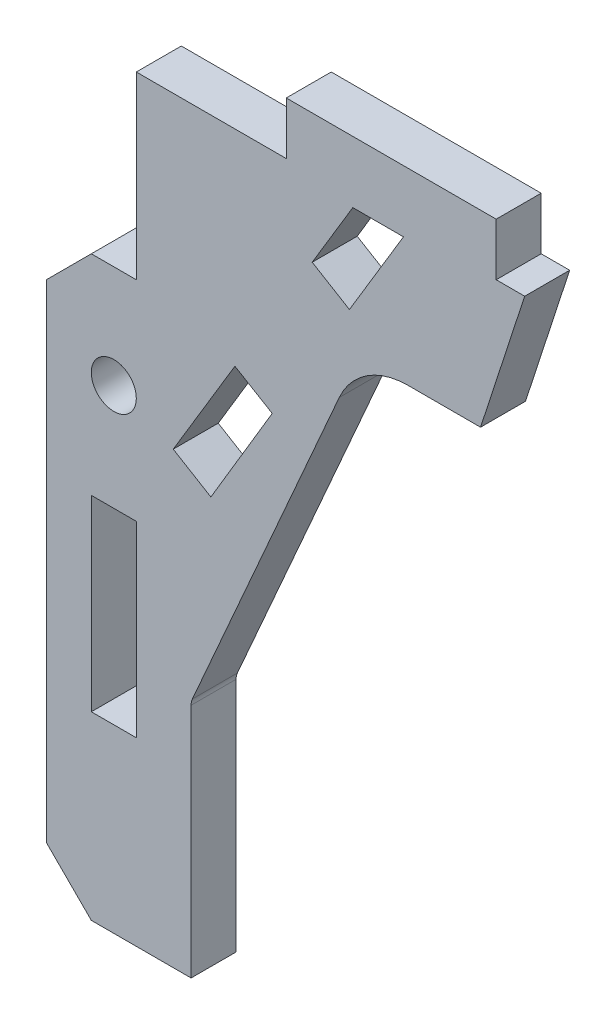
SolidWorks part; units mm, degrees
ref_plane "前视基准面" through (0, 0, 0) normal (0, 0, 1) x (1, 0, 0)
ref_plane "上视基准面" through (0, 0, 0) normal (0, 1, 0) x (1, 0, 0)
ref_plane "右视基准面" through (0, 0, 0) normal (1, 0, 0) x (0, 0, -1)
sketch "草图1" plane through (0, 0, 0) normal (0, 0, 1) x (1, 0, 0)
  line L1 (-25.4, 4.5488) -> (-22.4, 4.5488)
  line L3 (-25.4, -7.9512) -> (-25.4, 4.5488)
  line L5 (-22.4, 4.5488) -> (-22.4, -7.9512)
  line L7 (-22.4, -7.9512) -> (-25.4, -7.9512)
  line L9 (-0.9434, 20.7231) -> (-16.494, -16.074)
  line L11 (7.4, 21.9445) -> (0.8988, 21.9445)
  line L13 (9.4, 19.9445) -> (9.4, -20.3777)
  line L15 (-16.6475, -16.7224) -> (-16.8775, -20.2475)
  line L17 (-14.8817, -22.3777) -> (7.4, -22.3777)
  line L44 (-28.4, -17) -> (-25.4, -20)
  line L45 (-25.4, -20) -> (-22.4, -20)
  line L46 (-22.4, -20) -> (-22.4, -27.5)
  line L47 (-22.4, -27.5) -> (17.4, -27.5)
  line L48 (17.4, -27.5) -> (17.4, -20)
  line L49 (17.4, -20) -> (22.4, -20)
  line L50 (22.4, -20) -> (22.4, -5)
  line L51 (22.4, -5) -> (17.4, -5)
  line L52 (17.4, -5) -> (17.4, 10)
  line L53 (17.4, 10) -> (22.4, 10)
  line L54 (22.4, 10) -> (22.4, 20)
  line L55 (22.4, 20) -> (17.4, 20)
  line L56 (17.4, 20) -> (17.4, 30.5)
  line L57 (17.4, 30.5) -> (1.6, 30.5)
  line L58 (1.6, 30.5) -> (1.6, 34)
  line L59 (1.6, 34) -> (-12.4, 34)
  line L60 (-12.4, 34) -> (-12.4, 30.5)
  line L61 (-12.4, 30.5) -> (-22.4, 30.5)
  line L62 (-22.4, 30.5) -> (-22.4, 18.5)
  line L63 (-22.4, 18.5) -> (-25.4, 18.5)
  line L64 (-25.4, 18.5) -> (-28.4, 15.5)
  line L65 (-28.4, 15.5) -> (-28.4, -17)
  circle A1 centre (-23.9, 11.6451) radius 1.5
  arc A3 (0.8988, 21.9445) -> (-0.9434, 20.7231) centre (0.8988, 19.9445) ccw
  arc A5 (9.4, 19.9445) -> (7.4, 21.9445) centre (7.4, 19.9445) ccw
  arc A7 (-16.494, -16.074) -> (-16.6475, -16.7224) centre (-14.6518, -16.8525) ccw
  arc A9 (-16.8775, -20.2475) -> (-14.8817, -22.3777) centre (-14.8817, -20.3777) ccw
  arc A11 (7.4, -22.3777) -> (9.4, -20.3777) centre (7.4, -20.3777) ccw
extrude "凸台-拉伸1" add sketch "草图1" along normal blind 3
sketch "草图2" plane through (22.4, 0, 0) normal (1, 0, 0) x (0, 0, -1)
  line L4 (0, -20) -> (0, -5)
  line L5 (0, -5) -> (-3, -5)
  line L6 (-3, -5) -> (-3, -20)
  line L7 (-3, -20) -> (0, -20)
  line L8 (0, -20) -> (0, -5)
  line L9 (0, -5) -> (-3, -5)
  line L10 (-3, -5) -> (-3, -20)
  line L11 (-3, -20) -> (0, -20)
  line L12 (0, 10) -> (0, 20)
  line L13 (0, 20) -> (-3, 20)
  line L14 (-3, 20) -> (-3, 10)
  line L15 (-3, 10) -> (0, 10)
  line L16 (0, 10) -> (0, 20)
  line L17 (0, 20) -> (-3, 20)
  line L18 (-3, 20) -> (-3, 10)
  line L19 (-3, 10) -> (0, 10)
  dimension "D1" = 0
  dimension "D2" = 0
extrude "切除-拉伸1" cut sketch "草图2" against normal up to surface (5 mm away) up to face at (17.4, 2.5, 1.5)
sketch "草图4" plane through (0, 0, 0) normal (0, 0, -1) x (-1, 0, 0)
  line L0 (-7.4, 21.9445) -> (-17.4, 21.9445)
  line L1 (-17.4, -27.5) -> (-17.4, 30.5) construction
  line L2 (-17.4, 21.9445) -> (-17.4, 1.5)
  line L3 (-17.4, 1.5) -> (-9.4, 1.5)
  line L4 (-9.4, -20.3777) -> (-9.4, 19.9445) construction
  line L5 (-9.4, 1.5) -> (-7.4, 21.9445)
extrude "切除-拉伸2" cut sketch "草图4" against normal through all
sketch "草图5" plane through (0, 0, 0) normal (0, 0, -1) x (-1, 0, 0)
  line L0 (-7.4, -22.3777) -> (-17.4, -22.3777)
  line L1 (-17.4, -27.5) -> (-17.4, 1.5) construction
  line L2 (-17.4, -22.3777) -> (-17.4, 1.5)
  line L3 (-17.4, 1.5) -> (-9.4, 1.5)
  line L4 (-9.4, 1.5) -> (-7.4, -22.3777)
extrude "切除-拉伸3" cut sketch "草图5" against normal blind 10
sketch "草图6" plane through (0, 0, 0) normal (0, 0, -1) x (-1, 0, 0)
  line L0 (-0.8988, 21.9445) -> (10.5413, 21.9445)
  line L1 (10.5413, 21.9445) -> (16.598, -16.3917)
  line L2 (16.598, -16.3917) -> (-0.8988, 21.9445)
  arc A0 (16.6475, -16.7224) -> (16.494, -16.074) centre (14.6518, -16.8525) ccw construction
extrude "切除-拉伸4" cut sketch "草图6" against normal blind 10
sketch "草图8" plane through (0, 0, 0) normal (0, 0, -1) x (-1, 0, 0)
  line L0 (14.8817, -22.3777) -> (-17.4, -22.3777) construction
  line L1 (14.8817, -22.3777) -> (-17.4, -22.3777)
  line L2 (16.6475, -16.7224) -> (16.8775, -20.2475) construction
  line L3 (16.6475, -16.7224) -> (16.8775, -20.2475)
  line L4 (16.6475, -16.7224) -> (-17.4, -16.7224)
  line L5 (-17.4, -16.7224) -> (-17.4, -22.3777)
  arc A0 (14.8817, -22.3777) -> (16.8775, -20.2475) centre (14.8817, -20.3777) ccw construction
  arc A1 (14.8817, -22.3777) -> (16.8775, -20.2475) centre (14.8817, -20.3777) ccw
extrude "凸台-拉伸2" add sketch "草图8" against normal up to surface (3 mm away) up to face at (-10.7245, 3.6115, 3)
sketch "草图9" plane through (0, 0, 0) normal (0, 0, -1) x (-1, 0, 0)
  line L0 (16.6475, -16.7224) -> (-17.4, -16.7224) construction
  line L1 (16.6475, -16.7224) -> (-17.4, -16.7224)
  line L2 (16.598, -16.3917) -> (-17.4, -16.3917)
  line L3 (-17.4, -16.3917) -> (-17.4, -16.7224)
  arc A0 (16.6475, -16.7224) -> (16.598, -16.3917) centre (14.6518, -16.8525) ccw construction
  arc A1 (16.6475, -16.7224) -> (16.598, -16.3917) centre (14.6518, -16.8525) ccw
extrude "凸台-拉伸3" add sketch "草图9" against normal up to surface (3 mm away) up to face at (-10.1576, 6.5555, 3)
sketch "草图10" plane through (0, 0, 0) normal (0, 0, -1) x (-1, 0, 0)
  line L2 (16.598, -16.3917) -> (-17.4, -16.3917) construction
  line L3 (16.598, -16.3917) -> (-17.4, -16.3917)
  line L4 (-17.4, -16.3917) -> (-17.4, -18.3917)
  line L5 (16.598, -16.3917) -> (16.9139, -18.3917)
  line L6 (-17.4, -18.3917) -> (16.9139, -18.3917)
extrude "切除-拉伸5" cut sketch "草图10" against normal blind 8
fillet "圆角2" radius 5 1 edges at (-10.5413, 21.9445, 1.5)
sketch "草图11" plane through (0, 0, 0) normal (0, 0, -1) x (-1, 0, 0)
  line L0 (6.2692, 21.9445) -> (11.208, 17.7248)
  arc A0 (11.208, 17.7248) -> (6.2692, 21.9445) centre (6.2692, 16.9445) ccw construction
  arc A1 (11.208, 17.7248) -> (6.2692, 21.9445) centre (6.2692, 16.9445) ccw
extrude "凸台-拉伸4" add sketch "草图11" against normal up to surface (3 mm away) up to face at (-9.7037, 8.2232, 3)
fillet "圆角3" radius 2 2 edges at (-11.208, 17.7248, 1.5) (-6.2692, 21.9445, 1.5)
sketch "草图12" plane through (0, 0, 3) normal (0, 0, 1) x (1, 0, 0)
  line L0 (-6.8304, 21.4651) -> (-10.6468, 18.2042) construction
  line L1 (-7.9817, 20.4813) -> (-10.6468, 18.2042)
  line L2 (-11.3232, 16.9958) -> (-16.9139, -18.3917) construction
  line L3 (-11.3232, 16.9958) -> (-12.3413, 10.5513)
  line L4 (-7.9817, 20.4813) -> (-12.3413, 10.5513)
  arc A0 (-10.6468, 18.2042) -> (-11.3232, 16.9958) centre (-9.3477, 16.6837) ccw construction
  arc A1 (-10.6468, 18.2042) -> (-11.3232, 16.9958) centre (-9.3477, 16.6837) ccw
extrude "凸台-拉伸5" add sketch "草图12" against normal up to surface (3 mm away) up to face at (-23.9, -1.7012, 0)
fillet "圆角4" radius 2 2 edges at (-12.3413, 10.5513, 1.5) (-7.9817, 20.4813, 1.5)
sketch "草图14" plane through (0, 0, 3) normal (0, 0, 1) x (1, 0, 0)
  line L0 (-8.1658, 20.0621) -> (-6.3459, 24.2075)
  line L1 (-6.3459, 24.2075) -> (17.4, 24.2075)
  line L2 (17.4, 21.9445) -> (17.4, 30.5) construction
  line L3 (17.4, 24.2075) -> (17.4, 21.9445)
  line L4 (17.4, 21.9445) -> (-5.5312, 21.9445)
  line L5 (-6.8304, 21.4651) -> (-7.6337, 20.7787) construction
  line L6 (-6.8304, 21.4651) -> (-7.6337, 20.7787)
  arc A0 (-5.5312, 21.9445) -> (-6.8304, 21.4651) centre (-5.5312, 19.9445) ccw construction
  arc A1 (-5.5312, 21.9445) -> (-6.8304, 21.4651) centre (-5.5312, 19.9445) ccw
  arc A2 (-7.6337, 20.7787) -> (-8.1658, 20.0621) centre (-6.3345, 19.2582) ccw construction
  arc A3 (-7.6337, 20.7787) -> (-8.1658, 20.0621) centre (-6.3345, 19.2582) ccw
extrude "切除-拉伸6" cut sketch "草图14" against normal blind 6
sketch "草图15" plane through (0, 0, 3) normal (0, 0, 1) x (1, 0, 0)
  line L0 (17.4, -18.3917) -> (17.4, -22.3917)
  line L1 (17.4, -27.5) -> (17.4, -18.3917) construction
  line L2 (17.4, -22.3917) -> (-17.5459, -22.3917)
  line L3 (-16.9139, -18.3917) -> (17.4, -18.3917) construction
  line L5 (-16.9139, -18.3917) -> (-17.5459, -22.3917)
  line L6 (-16.9139, -18.3917) -> (17.4, -18.3917)
extrude "切除-拉伸7" cut sketch "草图15" against normal blind 10
sketch "草图16" plane through (0, 0, 3) normal (0, 0, 1) x (1, 0, 0)
  line L0 (17.4, -22.3917) -> (17.4, -24.3917)
  line L1 (17.4, -27.5) -> (17.4, -22.3917) construction
  line L2 (17.4, -24.3917) -> (-17.8618, -24.3917)
  line L5 (-17.5459, -22.3917) -> (-17.8618, -24.3917)
  line L6 (-17.5459, -22.3917) -> (17.4, -22.3917) construction
  line L7 (-17.5459, -22.3917) -> (17.4, -22.3917)
extrude "切除-拉伸8" cut sketch "草图16" against normal blind 10
sketch "草图17" plane through (0, 0, 3) normal (0, 0, 1) x (1, 0, 0)
  line L6 (17.4, 24.2075) -> (10.4, 24.2075)
  line L7 (17.4, 24.2075) -> (-6.3459, 24.2075) construction
  line L8 (10.4, 24.2075) -> (10.4, 30.5)
  line L9 (17.4, 30.5) -> (1.6, 30.5) construction
  line L10 (10.4, 30.5) -> (17.4, 30.5)
  line L11 (17.4, 30.5) -> (17.4, 24.2075)
extrude "切除-拉伸9" cut sketch "草图17" against normal blind 5
sketch "草图18" plane through (0, 0, 3) normal (0, 0, 1) x (1, 0, 0)
  line L0 (17.4, -27.5) -> (-2.5, -27.5)
  line L1 (-22.4, -27.5) -> (17.4, -27.5) construction
  line L2 (-2.5, -27.5) -> (-2.5, -24.3917)
  line L3 (-17.8618, -24.3917) -> (17.4, -24.3917) construction
  line L4 (-2.5, -24.3917) -> (17.4, -24.3917)
  line L5 (17.4, -24.3917) -> (17.4, -27.5)
extrude "切除-拉伸10" cut sketch "草图18" against normal through all
sketch "草图19" plane through (0, 0, 3) normal (0, 0, 1) x (1, 0, 0)
  line L0 (10.4, -14.5143) -> (10.4, -27.5)
  line L1 (-2.5, -27.5) -> (10.4, -27.5)
  line L2 (-17.8618, -24.3917) -> (-2.5, -24.3917) construction
  line L3 (-17.8618, -24.3917) -> (-2.5, -24.3917)
  line L4 (-12.3816, 10.296) -> (-17.8618, -24.3917) construction
  line L5 (-16.3013, -14.5143) -> (-17.8618, -24.3917)
  line L6 (-17.8618, -24.3917) -> (-16.3013, -14.5143)
  line L7 (-16.3013, -14.5143) -> (10.4, -14.5143)
  line L8 (-2.5, -27.5) -> (-2.5, -24.3917)
  line M2 (-2.5, -27.5) -> (-2.5, -24.3917)
  line M3 (-2.5, -24.3917) -> (-17.8618, -24.3917)
  line M4 (-17.8618, -24.3917) -> (-12.3816, 10.296)
extrude "凸台-拉伸6" add sketch "草图19" against normal up to surface (3 mm away) contours L7 L1 L0 M4 M3 M2 up to face at (-12.5921, 7.561, 0)
sketch "草图20" plane through (10.4, 0, 0) normal (1, 0, 0) x (0, 0, -1)
  line L4 (-3, -27.5) -> (0, -27.5)
  line L5 (0, -27.5) -> (0, -14.5143)
  line L6 (0, -14.5143) -> (-3, -14.5143)
  line L7 (-3, -14.5143) -> (-3, -27.5)
  line L8 (-3, -27.5) -> (0, -27.5)
  line L9 (0, -27.5) -> (0, -14.5143)
  line L10 (0, -14.5143) -> (-3, -14.5143)
  line L11 (-3, -14.5143) -> (-3, -27.5)
  dimension "D1" = 0
extrude "凸台-拉伸7" add sketch "草图20" along normal blind 7
sketch "草图22" plane through (0, 0, 3) normal (0, 0, 1) x (1, 0, 0)
  line L0 (-22.4, -27.5) -> (17.4, -27.5) construction
  line L1 (-22.4, -27.5) -> (17.4, -27.5)
  line L2 (17.4, -14.5143) -> (17.4, -27.5) construction
  line L3 (17.4, -14.5143) -> (17.4, -27.5)
  line L4 (-16.3013, -14.5143) -> (17.4, -14.5143) construction
  line L5 (-16.3013, -14.5143) -> (17.4, -14.5143)
  line L7 (17.4, -27.5) -> (17.4, -14)
  line L8 (17.4, -14) -> (-16.2201, -14)
  line L9 (-12.3816, 10.296) -> (-16.3013, -14.5143) construction
  line L10 (-16.2201, -14) -> (-16.3013, -14.5143)
  line M1 (17.4, -14.5143) -> (-16.3013, -14.5143)
  line M2 (-16.3013, -14.5143) -> (-12.3816, 10.296)
extrude "凸台-拉伸9" add sketch "草图22" against normal up to surface (3 mm away) contours L7 L8 M2 M1 up to face at (-10.5241, 8.5488, 0)
sketch "草图23" plane through (17.4, 0, 0) normal (1, 0, 0) x (0, 0, -1)
  line L0 (-3, -14) -> (-3, -27.5) construction
  line L1 (-3, -16.75) -> (-3, -24.75)
  line L2 (0, -27.5) -> (0, -14) construction
  line L3 (0, -24.75) -> (0, -16.75)
  line L4 (-3, -20.75) -> (-3, -16.75)
  line L5 (-3, -16.75) -> (0, -16.75)
  line L6 (0, -16.75) -> (0, -24.75)
  line L7 (0, -24.75) -> (-3, -24.75)
  line M1 (-3, -14) -> (-3, -27.5)
  line M3 (0, -27.5) -> (0, -14)
extrude "凸台-拉伸10" add sketch "草图23" along normal blind 5 contours L7 L5 L1 M3 M1
sketch "草图25" plane through (0, 0, 3) normal (0, 0, 1) x (1, 0, 0)
  line L0 (10.4, 24.2075) -> (-6.3459, 24.2075) construction
  line L1 (10.4, 24.2075) -> (-6.3459, 24.2075)
  line L2 (-12.2374, 10.7879) -> (-6.3459, 24.2075) construction
  line L3 (-7.5518, 21.4605) -> (-6.3459, 24.2075)
  line L4 (-6.3459, 24.2075) -> (-7.5518, 21.4605)
  line L5 (-7.5518, 21.4605) -> (10.4, 21.4605)
  line L6 (10.4, 21.4605) -> (10.4, 24.2075)
  line M5 (-12.2374, 10.7879) -> (-6.3459, 24.2075)
  line M6 (-6.3459, 24.2075) -> (10.4, 24.2075)
extrude "凸台-拉伸11" add sketch "草图25" against normal up to surface (3 mm away) contours L5 L6 M6 M5 up to face at (-5.45, 3.7085, 0)
fillet "圆角7" radius 5 1 edges at (-7.5518, 21.4605, 1.5)
sketch "草图26" plane through (0, 0, 3) normal (0, 0, 1) x (1, 0, 0)
  line L2 (-16.2201, -14) -> (-17.4685, -21.902)
  line L3 (-17.4685, -21.902) -> (12.3226, -22.559)
  line L4 (12.3226, -22.559) -> (12.3226, -14)
  line L5 (17.4, -14) -> (-16.2201, -14) construction
  line L6 (12.3226, -14) -> (-16.2201, -14)
extrude "切除-拉伸11" cut sketch "草图26" against normal blind 10
fillet "圆角8" radius 10 1 edges at (-17.4685, -21.902, 1.5)
sketch "草图30" plane through (0, 0, 3) normal (0, 0, 1) x (1, 0, 0)
  line L0 (17.4, -14) -> (12.3226, -14) construction
  line L1 (13.4, -14) -> (12.3226, -14)
  line L3 (13.4, -14) -> (13.4, -22.5658)
  line L4 (13.4, -22.5658) -> (12.3226, -22.559)
  line L5 (12.3226, -22.559) -> (12.3226, -14)
extrude "切除-拉伸13" cut sketch "草图30" against normal blind 10
sketch "草图32" plane through (13.4, 0, 0) normal (-1, 0, 0) x (0, 0, 1)
  line L4 (0, -22.5658) -> (3, -22.5658)
  line L5 (3, -22.5658) -> (3, -14)
  line L6 (3, -14) -> (0, -14)
  line L7 (0, -14) -> (0, -22.5658)
  line L8 (0, -22.5658) -> (3, -22.5658)
  line L9 (3, -22.5658) -> (3, -14)
  line L10 (3, -14) -> (0, -14)
  line L11 (0, -14) -> (0, -22.5658)
  dimension "D1" = 0
extrude "凸台-拉伸12" add sketch "草图32" along normal blind 0.5
fillet "圆角10" radius 3 1 edges at (12.9, -22.5626, 1.5)
sketch "草图33" plane through (10.4, 0, 0) normal (1, 0, 0) x (0, 0, -1)
  line L4 (0, 30.5) -> (-3, 30.5)
  line L5 (-3, 30.5) -> (-3, 21.4605)
  line L6 (-3, 21.4605) -> (0, 21.4605)
  line L7 (0, 21.4605) -> (0, 30.5)
  line L8 (0, 30.5) -> (-3, 30.5)
  line L9 (-3, 30.5) -> (-3, 21.4605)
  line L10 (-3, 21.4605) -> (0, 21.4605)
  line L11 (0, 21.4605) -> (0, 30.5)
  dimension "D1" = 0
extrude "切除-拉伸14" cut sketch "草图33" against normal blind 5
sketch "草图34" plane through (0, 0, 3) normal (0, 0, 1) x (1, 0, 0)
  line L0 (5.4, 30.5) -> (1.6, 30.5) construction
  line L1 (5.4, 30.5) -> (3.5, 30.5)
  line L2 (5.4, 30.5) -> (5.4, 21.4605) construction
  line L3 (5.4, 30.5) -> (5.4, 21.4605)
  line L4 (3.5, 30.5) -> (0.5568, 21.4605)
  line L5 (-4.2863, 21.4605) -> (5.4, 21.4605) construction
  line L6 (0.5568, 21.4605) -> (5.4, 21.4605)
extrude "切除-拉伸15" cut sketch "草图34" against normal blind 10
sketch "草图35" plane through (0, 0, 3) normal (0, 0, 1) x (1, 0, 0)
  line L0 (-15.8049, -12.1577) -> (-15.8035, -27.5)
  line L1 (-22.4, -27.5) -> (17.4, -27.5) construction
  line L2 (-6.0253, -22.1544) -> (9.8339, -22.5041) construction
  line L3 (-6.0253, -22.1544) -> (9.8339, -22.5041)
  line L4 (12.9, -19.5048) -> (12.9, -14) construction
  line L5 (12.9, -19.5048) -> (12.9, -14)
  line L6 (17.4, -14) -> (12.9, -14) construction
  line L7 (17.4, -14) -> (12.9, -14)
  line L8 (17.4, -14) -> (17.4, -16.75) construction
  line L9 (17.4, -14) -> (17.4, -16.75)
  line L10 (22.4, -16.75) -> (17.4, -16.75) construction
  line L11 (22.4, -16.75) -> (17.4, -16.75)
  line L12 (22.4, -16.75) -> (22.4, -24.75) construction
  line L13 (22.4, -16.75) -> (22.4, -24.75)
  line L14 (22.4, -24.75) -> (17.4, -24.75) construction
  line L15 (22.4, -24.75) -> (17.4, -24.75)
  line L16 (17.4, -24.75) -> (17.4, -27.5) construction
  line L17 (17.4, -24.75) -> (17.4, -27.5)
  line L18 (-15.8035, -27.5) -> (17.4, -27.5)
  arc A0 (-15.6823, -10.5963) -> (-6.0253, -22.1544) centre (-5.8049, -12.1568) ccw construction
  arc A1 (-15.8049, -12.1577) -> (-6.0253, -22.1544) centre (-5.8049, -12.1568) ccw
  arc A2 (9.8339, -22.5041) -> (12.9, -19.5048) centre (9.9, -19.5048) ccw construction
  arc A3 (9.8339, -22.5041) -> (12.9, -19.5048) centre (9.9, -19.5048) ccw
extrude "切除-拉伸16" cut sketch "草图35" against normal blind 10
extrude "切除-拉伸18" cut sketch "草图37" against normal blind 3
sketch "草图37" plane through (173.3432, -117.9586, 0) normal (0, 0, -1) x (1, 0, 0)
  line L8 (-181.3043, -147.8456) -> (-177.9262, -147.8456)
  line L9 (-177.9262, -147.8456) -> (-181.5302, -141.8447)
  line L10 (-181.5302, -141.8447) -> (-184.0128, -143.3357)
  line L11 (-184.0128, -143.3357) -> (-181.3043, -147.8456)
  line L16 (-189.1671, -134.7534) -> (-186.6782, -133.2716)
  line L17 (-186.6782, -133.2716) -> (-190.7706, -126.3976)
  line L18 (-190.7706, -126.3976) -> (-193.2802, -127.9048)
  line L19 (-193.2802, -127.9048) -> (-189.1671, -134.7534)
sketch "草图38" plane through (0, 0, 3) normal (0, 0, 1) x (1, 0, 0)
  line L0 (-22.4, -20) -> (-22.4, -27.5) construction
  line L1 (-22.4, -20) -> (-22.4, -27.5)
  line L2 (-22.4, -20) -> (-15.8042, -20)
  line L4 (-15.8049, -12.1577) -> (-15.8035, -27.5) construction
  line L5 (-15.8042, -20) -> (-15.8035, -27.5)
  line L6 (-15.8035, -27.5) -> (-22.4, -27.5)
extrude "切除-拉伸19" cut sketch "草图38" against normal blind 10
sketch "草图39" plane through (0, 0, 3) normal (0, 0, 1) x (1, 0, 0)
  line L1 (-12.3816, 10.296) -> (-12.2374, 10.7879)
  line L2 (-12.2374, 10.7879) -> (-18.7465, -4.0382)
  line L3 (-18.7465, -4.0382) -> (-18.7465, -20)
  line L4 (-25.4, -20) -> (-15.8042, -20) construction
  line L5 (-18.7465, -20) -> (-15.8042, -20)
  line L6 (-12.3816, 10.296) -> (-15.6823, -10.5963) construction
  line L7 (-12.3816, 10.296) -> (-15.6823, -10.5963)
  line L8 (-15.8049, -12.1577) -> (-15.8042, -20) construction
  line L9 (-15.8049, -12.1577) -> (-15.8042, -20)
  arc A0 (-15.6823, -10.5963) -> (-15.8049, -12.1577) centre (-5.8049, -12.1568) ccw construction
  arc A1 (-15.6823, -10.5963) -> (-15.8049, -12.1577) centre (-5.8049, -12.1568) ccw
extrude "切除-拉伸20" cut sketch "草图39" against normal blind 10
fillet "圆角11" radius 1 1 edges at (-18.7465, -4.0382, 1.5)
